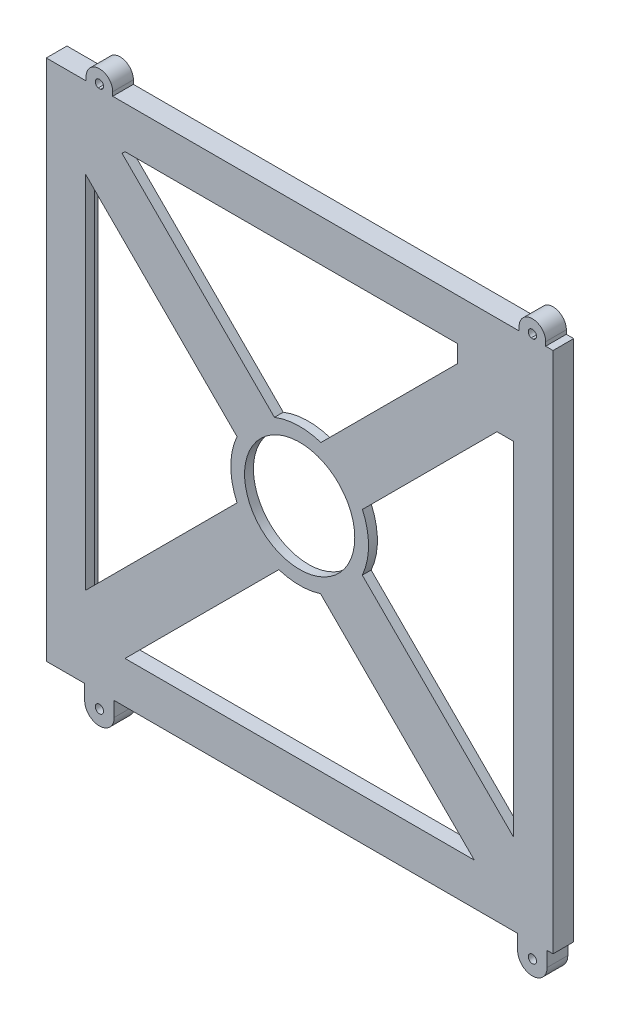
SolidWorks part; units mm, degrees
ref_plane "Plan de face" through (0, 0, 0) normal (0, 0, 1) x (1, 0, 0)
ref_plane "Plan de dessus" through (0, 0, 0) normal (0, 1, 0) x (1, 0, 0)
ref_plane "Plan de droite" through (0, 0, 0) normal (1, 0, 0) x (0, 0, -1)
sketch "Esquisse1" plane through (0, 0, 0) normal (0, 0, 1) x (1, 0, 0)
  line L0 (123.75, 127.75) -> (-123.75, 127.75) construction
  line L1 (128.75, -132.75) -> (88.75, -132.75)
  line L2 (128.75, -132.75) -> (128.75, -91.5073)
  line L3 (128.75, 132.75) -> (80.2566, 132.75)
  line L4 (-128.75, -132.75) -> (-128.75, -91.5073)
  line L5 (128.75, -132.75) -> (-128.75, 132.75) construction
  line L6 (128.75, 132.75) -> (-128.75, -132.75) construction
  line L7 (123.75, -127.75) -> (123.75, 127.75) construction
  line L8 (128.75, 82.75) -> (100.2566, 82.75)
  line L9 (80.2566, 102.75) -> (80.2566, 132.75)
  line L10 (100.2566, 82.75) -> (80.2566, 102.75)
  line L11 (-88.75, 132.75) -> (-88.75, 111.5073)
  line L12 (-108.75, 91.5073) -> (-128.75, 91.5073)
  line L13 (-128.75, -91.5073) -> (-108.75, -91.5073)
  line L14 (-88.75, -111.5073) -> (-88.75, -132.75)
  line L15 (88.75, -132.75) -> (88.75, -111.5073)
  line L16 (108.75, -91.5073) -> (128.75, -91.5073)
  line L19 (88.75, -111.5073) -> (108.75, -91.5073)
  line L20 (-108.75, -91.5073) -> (-88.75, -111.5073)
  line L21 (-88.75, 111.5073) -> (-108.75, 91.5073)
  line L22 (-88.75, 132.75) -> (-128.75, 132.75)
  line L23 (-128.75, 91.5073) -> (-128.75, 132.75)
  line L24 (-88.75, -132.75) -> (-128.75, -132.75)
  line L25 (128.75, 82.75) -> (128.75, 132.75)
  point P0 (0, 0)
  point P11 (80.2566, 82.75)
  point P16 (-88.75, 91.5073)
  point P19 (-88.75, -91.5073)
  point P22 (88.75, -91.5073)
  dimension "D1" = 5
  dimension "D2" = 5
  dimension "D3" = 50
  dimension "D4" = 40
  dimension "D5" = 40
  dimension "D7" = 40
extrude "Boss.-Extru.1" add sketch "Esquisse1" along normal blind 5
sketch "Esquisse2" plane through (0, 0, 0) normal (0, 0, -1) x (-1, 0, 0)
  line L0 (-80.2566, 127.75) -> (-80.2566, 132.75)
  line L1 (-123.75, 127.75) -> (123.75, 127.75) construction
  line L2 (-80.2566, 132.75) -> (-80.2566, 102.75) construction
  line L3 (-80.2566, 132.75) -> (-128.75, 132.75)
  line L4 (-128.75, 132.75) -> (-128.75, 82.75)
  line L5 (-128.75, 82.75) -> (-128.75, 132.75) construction
  line L6 (-128.75, 82.75) -> (-123.75, 82.75)
  line L7 (-123.75, -127.75) -> (-123.75, 127.75) construction
  line L8 (-100.2566, 82.75) -> (-128.75, 82.75) construction
  line L9 (-123.75, 82.75) -> (-123.75, 127.75)
  line L10 (-123.75, 127.75) -> (-80.2566, 127.75)
  line L11 (-123.75, -127.75) -> (-88.75, -127.75)
  line L12 (123.75, -127.75) -> (-123.75, -127.75) construction
  line L13 (-88.75, -127.75) -> (-88.75, -132.75)
  line L14 (-88.75, -132.75) -> (-128.75, -132.75)
  line L15 (-128.75, -132.75) -> (-128.75, -91.5073)
  line L16 (-128.75, -91.5073) -> (-123.75, -91.5073)
  line L17 (-128.75, -91.5073) -> (-108.75, -91.5073) construction
  line L18 (-123.75, -91.5073) -> (-123.75, -127.75)
  line L19 (88.75, -127.75) -> (88.75, -132.75)
  line L20 (88.75, -132.75) -> (88.75, -111.5073) construction
  line L21 (88.75, -132.75) -> (128.75, -132.75)
  line L22 (128.75, -132.75) -> (128.75, -91.5073)
  line L23 (128.75, -91.5073) -> (123.75, -91.5073)
  line L24 (123.75, 127.75) -> (123.75, -127.75) construction
  line L25 (108.75, -91.5073) -> (128.75, -91.5073) construction
  line L26 (123.75, -91.5073) -> (123.75, -127.75)
  line L27 (123.75, -127.75) -> (88.75, -127.75)
  line L28 (128.75, 132.75) -> (88.75, 132.75)
  line L29 (88.75, 132.75) -> (88.75, 127.75)
  line L31 (88.75, 127.75) -> (123.75, 127.75)
  line L32 (123.75, 127.75) -> (123.75, 91.5073)
  line L33 (128.75, 91.5073) -> (108.75, 91.5073) construction
  line L34 (123.75, 91.5073) -> (128.75, 91.5073)
  line L35 (128.75, 91.5073) -> (128.75, 132.75)
  line L36 (-88.75, -111.5073) -> (-88.75, -132.75) construction
extrude "Boss.-Extru.2" add sketch "Esquisse2" along normal blind 3
sketch "Esquisse3" plane through (0, 0, 3) normal (0, 0, 1) x (1, 0, 0)
  line L0 (110, 82.75) -> (110, 110)
  line L1 (100.2566, 82.75) -> (128.75, 82.75) construction
  line L2 (110, -110) -> (110, 110) construction
  line L3 (110, 110) -> (80.2566, 110)
  line L4 (80.2566, 132.75) -> (80.2566, 102.75) construction
  line L5 (110, 110) -> (-110, 110) construction
  line L6 (80.2566, 110) -> (80.2566, 102.75)
  line L7 (80.2566, 102.75) -> (100.2566, 82.75) construction
  line L8 (80.2566, 102.75) -> (100.2566, 82.75)
  line L9 (100.2566, 82.75) -> (110, 82.75)
  line L10 (-90.2573, 110) -> (-110, 110)
  line L11 (-108.75, 91.5073) -> (-88.75, 111.5073) construction
  line L12 (-110, 110) -> (-110, 91.5073)
  line L13 (-128.75, 91.5073) -> (-108.75, 91.5073) construction
  line L14 (-110, 110) -> (-110, -110) construction
  line L15 (-110, 91.5073) -> (-108.75, 91.5073)
  line L16 (-108.75, 91.5073) -> (-90.2573, 110)
  line L17 (-110, -110) -> (-110, -91.5073)
  line L18 (-108.75, -91.5073) -> (-128.75, -91.5073) construction
  line L19 (-110, -91.5073) -> (-108.75, -91.5073)
  line L20 (-108.75, -91.5073) -> (-90.2573, -110)
  line L23 (110, -91.5073) -> (110, -110)
  line L24 (128.75, -91.5073) -> (108.75, -91.5073) construction
  line L25 (110, -110) -> (90.2573, -110)
  line L26 (108.75, -91.5073) -> (88.75, -111.5073) construction
  line L27 (-110, -110) -> (110, -110) construction
  line L28 (90.2573, -110) -> (108.75, -91.5073)
  line L29 (108.75, -91.5073) -> (110, -91.5073)
  line L30 (-110, -110) -> (-90.2573, -110)
extrude "Enlèv. mat.-Extru.2" cut sketch "Esquisse3" against normal through all
sketch "Esquisse4" plane through (0, 0, 3) normal (0, 0, -1) x (-1, 0, 0)
  circle A0 centre (-107.5, 107.5) radius 1.6 construction
  circle A1 centre (-107.5, -107.5) radius 1.6 construction
  circle A2 centre (107.5, -107.5) radius 1.6 construction
  circle A3 centre (107.5, 107.5) radius 1.6 construction
  circle A4 centre (-107.5, 107.5) radius 1.6
  circle A5 centre (-107.5, -107.5) radius 1.6
  circle A6 centre (107.5, -107.5) radius 1.6
  circle A7 centre (107.5, 107.5) radius 1.6
extrude "Boss.-Extru.3" add sketch "Esquisse4" along normal blind 3
sketch "Esquisse5" plane through (0, 91.5073, 0) normal (0, -1, 0) x (1, 0, 0)
  line L8 (-123.75, 0) -> (-110, 0)
  line L9 (-110, 0) -> (-110, 3)
  line L10 (-110, 3) -> (-108.75, 3)
  line L11 (-108.75, 3) -> (-108.75, 5)
  line L12 (-108.75, 5) -> (-128.75, 5)
  line L13 (-128.75, 5) -> (-128.75, -3)
  line L14 (-128.75, -3) -> (-123.75, -3)
  line L15 (-123.75, -3) -> (-123.75, 0)
  line L16 (-123.75, 0) -> (-110, 0)
  line L17 (-110, 0) -> (-110, 3)
  line L18 (-110, 3) -> (-108.75, 3)
  line L19 (-108.75, 3) -> (-108.75, 5)
  line L20 (-108.75, 5) -> (-128.75, 5)
  line L21 (-128.75, 5) -> (-128.75, -3)
  line L22 (-128.75, -3) -> (-123.75, -3)
  line L23 (-123.75, -3) -> (-123.75, 0)
  dimension "D1" = 0
extrude "Boss.-Extru.4" add sketch "Esquisse5" along normal up to surface (183.0146 mm away)
sketch "Esquisse7" plane through (-88.75, 0, 0) normal (1, 0, 0) x (0, 0, -1)
  line L6 (0, 111.5073) -> (0, 127.75)
  line L7 (0, 127.75) -> (3, 127.75)
  line L8 (3, 127.75) -> (3, 132.75)
  line L9 (3, 132.75) -> (-5, 132.75)
  line L10 (-5, 132.75) -> (-5, 111.5073)
  line L11 (-5, 111.5073) -> (0, 111.5073)
  line L12 (0, 111.5073) -> (0, 127.75)
  line L13 (0, 127.75) -> (3, 127.75)
  line L14 (3, 127.75) -> (3, 132.75)
  line L15 (3, 132.75) -> (-5, 132.75)
  line L16 (-5, 132.75) -> (-5, 111.5073)
  line L17 (-5, 111.5073) -> (0, 111.5073)
  dimension "D1" = 0
extrude "Boss.-Extru.6" add sketch "Esquisse7" along normal up to surface (169.0066 mm away) up to face at (80.2566, 118.3125, 1.25)
sketch "Esquisse8" plane through (0, -91.5073, 0) normal (0, 1, 0) x (1, 0, 0)
  line L8 (123.75, 0) -> (110, 0)
  line L9 (110, 0) -> (110, -3)
  line L10 (110, -3) -> (108.75, -3)
  line L11 (108.75, -3) -> (108.75, -5)
  line L12 (108.75, -5) -> (128.75, -5)
  line L13 (128.75, -5) -> (128.75, 3)
  line L14 (128.75, 3) -> (123.75, 3)
  line L15 (123.75, 3) -> (123.75, 0)
  line L16 (123.75, 0) -> (110, 0)
  line L17 (110, 0) -> (110, -3)
  line L18 (110, -3) -> (108.75, -3)
  line L19 (108.75, -3) -> (108.75, -5)
  line L20 (108.75, -5) -> (128.75, -5)
  line L21 (128.75, -5) -> (128.75, 3)
  line L22 (128.75, 3) -> (123.75, 3)
  line L23 (123.75, 3) -> (123.75, 0)
  dimension "D1" = 0
extrude "Boss.-Extru.7" add sketch "Esquisse8" along normal up to surface (174.2573 mm away) up to face at (115.6891, 82.75, 1.25)
sketch "Esquisse9" plane through (88.75, 0, 0) normal (-1, 0, 0) x (0, 0, 1)
  line L6 (0, -111.5073) -> (0, -127.75)
  line L7 (0, -127.75) -> (-3, -127.75)
  line L8 (-3, -127.75) -> (-3, -132.75)
  line L9 (-3, -132.75) -> (5, -132.75)
  line L10 (5, -132.75) -> (5, -111.5073)
  line L11 (5, -111.5073) -> (0, -111.5073)
  line L12 (0, -111.5073) -> (0, -127.75)
  line L13 (0, -127.75) -> (-3, -127.75)
  line L14 (-3, -127.75) -> (-3, -132.75)
  line L15 (-3, -132.75) -> (5, -132.75)
  line L16 (5, -132.75) -> (5, -111.5073)
  line L17 (5, -111.5073) -> (0, -111.5073)
  dimension "D1" = 0
extrude "Boss.-Extru.8" add sketch "Esquisse9" along normal up to surface (177.5 mm away)
sketch "Esquisse10" plane through (0, 0, 5) normal (0, 0, 1) x (1, 0, 0)
  line L0 (110, 110) -> (0, 0) construction
  line L1 (0, 0) -> (110, -110) construction
  line L2 (0, 0) -> (-110, 110) construction
  line L3 (-110, -110) -> (0, 0) construction
  line L4 (100.2566, 82.75) -> (31.9024, 14.3958)
  line L5 (80.2566, 102.75) -> (10.799, 33.2924)
  line L6 (-108.75, 91.5073) -> (-31.8199, 14.5772)
  line L7 (-90.2573, 110) -> (-12.8235, 32.5662)
  line L8 (-88.75, -111.5073) -> (-10.5992, -33.3565)
  line L9 (-108.75, -91.5073) -> (-31.8199, -14.5772)
  line L10 (88.75, -111.5073) -> (10.5992, -33.3565)
  line L11 (108.75, -91.5073) -> (31.8199, -14.5772)
  line L12 (-90.2573, 110) -> (-108.75, 91.5073)
  line L13 (-108.75, -91.5073) -> (-88.75, -111.5073)
  line L14 (88.75, -111.5073) -> (108.75, -91.5073)
  line L15 (100.2566, 82.75) -> (80.2566, 102.75)
  arc A0 (10.799, 33.2924) -> (-12.8235, 32.5662) centre (0, 0) ccw
  arc A1 (31.8199, -14.5772) -> (31.9024, 14.3958) centre (0, 0) ccw
  arc A2 (-10.5992, -33.3565) -> (10.5992, -33.3565) centre (0, 0) ccw
  arc A3 (-31.8199, 14.5772) -> (-31.8199, -14.5772) centre (0, 0) ccw
  circle A4 centre (0, 0) radius 28
  dimension "D1" = 70
  dimension "D2" = 7
extrude "Boss.-Extru.9" add sketch "Esquisse10" against normal up to surface (2 mm away)
sketch "Esquisse11" plane through (0, 0, 5) normal (0, 0, 1) x (1, 0, 0)
  line L0 (80.2566, 111.5073) -> (80.2566, 102.75) construction
  line L1 (80.2566, 102.75) -> (10.799, 33.2924) construction
  line L2 (80.2566, 111.5073) -> (-88.75, 111.5073) construction
  line L3 (-12.8235, 32.5662) -> (-90.2573, 110) construction
  line L4 (-128.75, 132.75) -> (-128.75, -132.75)
  line L5 (-128.75, -132.75) -> (128.75, -132.75)
  line L6 (128.75, -132.75) -> (128.75, 132.75)
  line L7 (128.75, 132.75) -> (-128.75, 132.75)
  line L8 (-128.75, 132.75) -> (-128.75, -132.75)
  line L9 (-128.75, -132.75) -> (128.75, -132.75)
  line L10 (128.75, -132.75) -> (128.75, 132.75)
  line L11 (128.75, 132.75) -> (-128.75, 132.75)
  line L12 (-108.75, 91.5073) -> (-31.8199, 14.5772) construction
  line L13 (-108.75, -91.5073) -> (-108.75, 91.5073) construction
  line L14 (-31.8199, -14.5772) -> (-108.75, -91.5073) construction
  line L15 (-88.75, -111.5073) -> (-10.5992, -33.3565) construction
  line L16 (-88.75, -111.5073) -> (88.75, -111.5073) construction
  line L17 (10.5992, -33.3565) -> (88.75, -111.5073) construction
  line L18 (108.75, -91.5073) -> (31.8199, -14.5772) construction
  line L19 (108.75, 82.75) -> (108.75, -91.5073) construction
  line L20 (31.9024, 14.3958) -> (100.2566, 82.75) construction
  line L21 (100.2566, 82.75) -> (108.75, 82.75) construction
  line L22 (80.2566, 111.5073) -> (80.2566, 102.75)
  line L23 (80.2566, 102.75) -> (10.799, 33.2924)
  line L24 (80.2566, 111.5073) -> (-88.75, 111.5073)
  line L25 (-12.8235, 32.5662) -> (-90.2573, 110)
  line L26 (-108.75, 91.5073) -> (-31.8199, 14.5772)
  line L27 (-108.75, -91.5073) -> (-108.75, 91.5073)
  line L28 (-31.8199, -14.5772) -> (-108.75, -91.5073)
  line L29 (-88.75, -111.5073) -> (-10.5992, -33.3565)
  line L30 (-88.75, -111.5073) -> (88.75, -111.5073)
  line L31 (10.5992, -33.3565) -> (88.75, -111.5073)
  line L32 (108.75, -91.5073) -> (31.8199, -14.5772)
  line L33 (108.75, 82.75) -> (108.75, -91.5073)
  line L34 (31.9024, 14.3958) -> (100.2566, 82.75)
  line L35 (100.2566, 82.75) -> (108.75, 82.75)
  line L36 (-90.2573, 110) -> (-88.75, 111.5073) construction
  line L37 (-90.2573, 110) -> (-88.75, 111.5073)
  circle A0 centre (0, 0) radius 28 construction
  arc A1 (10.799, 33.2924) -> (-12.8235, 32.5662) centre (0, 0) ccw construction
  arc A2 (-31.8199, 14.5772) -> (-31.8199, -14.5772) centre (0, 0) ccw construction
  arc A3 (-10.5992, -33.3565) -> (10.5992, -33.3565) centre (0, 0) ccw construction
  arc A4 (31.8199, -14.5772) -> (31.9024, 14.3958) centre (0, 0) ccw construction
  circle A5 centre (0, 0) radius 28
  arc A6 (10.799, 33.2924) -> (-12.8235, 32.5662) centre (0, 0) ccw
  arc A7 (-31.8199, 14.5772) -> (-31.8199, -14.5772) centre (0, 0) ccw
  arc A8 (-10.5992, -33.3565) -> (10.5992, -33.3565) centre (0, 0) ccw
  arc A9 (31.8199, -14.5772) -> (31.9024, 14.3958) centre (0, 0) ccw
  dimension "D1" = 0
extrude "Boss.-Extru.11" add sketch "Esquisse11" along normal blind 2.5
sketch "Esquisse12" plane through (0, 0, -3) normal (0, 0, -1) x (-1, 0, 0)
  line L0 (109.25, -140.25) -> (109.25, -132.75)
  line L1 (-128.75, -132.75) -> (128.75, -132.75) construction
  line L2 (109.25, -132.75) -> (94.25, -132.75)
  line L3 (94.25, -132.75) -> (94.25, -140.25)
  line L4 (128.75, -132.75) -> (128.75, 132.75) construction
  line L5 (-110.75, -140.25) -> (-110.75, -132.75)
  line L6 (-110.75, -132.75) -> (-125.75, -132.75)
  line L7 (-125.75, -132.75) -> (-125.75, -140.25)
  line L8 (-128.75, 132.75) -> (-128.75, -132.75) construction
  circle A0 centre (101.75, -140.25) radius 2.1
  arc A1 (94.25, -140.25) -> (109.25, -140.25) centre (101.75, -140.25) ccw
  circle A2 centre (-118.25, -140.25) radius 2.1
  arc A3 (-125.75, -140.25) -> (-110.75, -140.25) centre (-118.25, -140.25) ccw
  dimension "D1" = 19.5
  dimension "D2" = 4.2
  dimension "D4" = 4.2
  dimension "D3" = 3
extrude "Boss.-Extru.12" add sketch "Esquisse12" against normal up to surface (10.5 mm away) up to face at (-3.4303, 83.9462, 7.5)
sketch "Esquisse13" plane through (0, 0, -3) normal (0, 0, -1) x (-1, 0, 0)
  circle A0 centre (-118.25, -140.25) radius 5.1
  circle A2 centre (101.75, -140.25) radius 5.1
  dimension "D1" = 10.2
  dimension "D2" = 10.2
extrude "Enlèv. mat.-Extru.3" cut sketch "Esquisse13" against normal blind 5
sketch "Esquisse14" plane through (0, 0, -3) normal (0, 0, -1) x (-1, 0, 0)
  line L0 (-125, 134.75) -> (-125, 132.75)
  line L1 (128.75, 132.75) -> (-128.75, 132.75) construction
  line L2 (-125, 132.75) -> (-111.5, 132.75)
  line L3 (-111.5, 132.75) -> (-111.5, 134.75)
  line L4 (95, 134.75) -> (95, 132.75)
  line L5 (95, 132.75) -> (108.5, 132.75)
  line L6 (108.5, 132.75) -> (108.5, 134.75)
  circle A1 centre (-118.25, 134.75) radius 2.1
  arc A2 (-111.5, 134.75) -> (-125, 134.75) centre (-118.25, 134.75) ccw
  arc A3 (108.5, 134.75) -> (95, 134.75) centre (101.75, 134.75) ccw
  circle A4 centre (101.75, 134.75) radius 2.1
  line M17 (128.75, 132.75) -> (-128.75, 132.75)
  dimension "D1" = 4.2
  dimension "D2" = 13.5
  dimension "D3" = 13.5
  dimension "D4" = 4.2
extrude "Boss.-Extru.13" add sketch "Esquisse14" against normal up to surface (10.5 mm away) contours A4 L6 A3 L4 M17 | L3 A2 L0 A1 M17
sketch "Esquisse15" plane through (0, 0, -3) normal (0, 0, -1) x (-1, 0, 0)
  circle A0 centre (101.75, 134.75) radius 5.1
  circle A1 centre (-118.25, 134.75) radius 5.1
  dimension "D1" = 10.2
  dimension "D2" = 10.2
extrude "Enlèv. mat.-Extru.4" cut sketch "Esquisse15" against normal blind 5
fillet "Congé1" radius 1 3 edges at (105.9, -107.5, 0) (-109.1, -107.5, 0) (-109.1, 107.5, 0)
